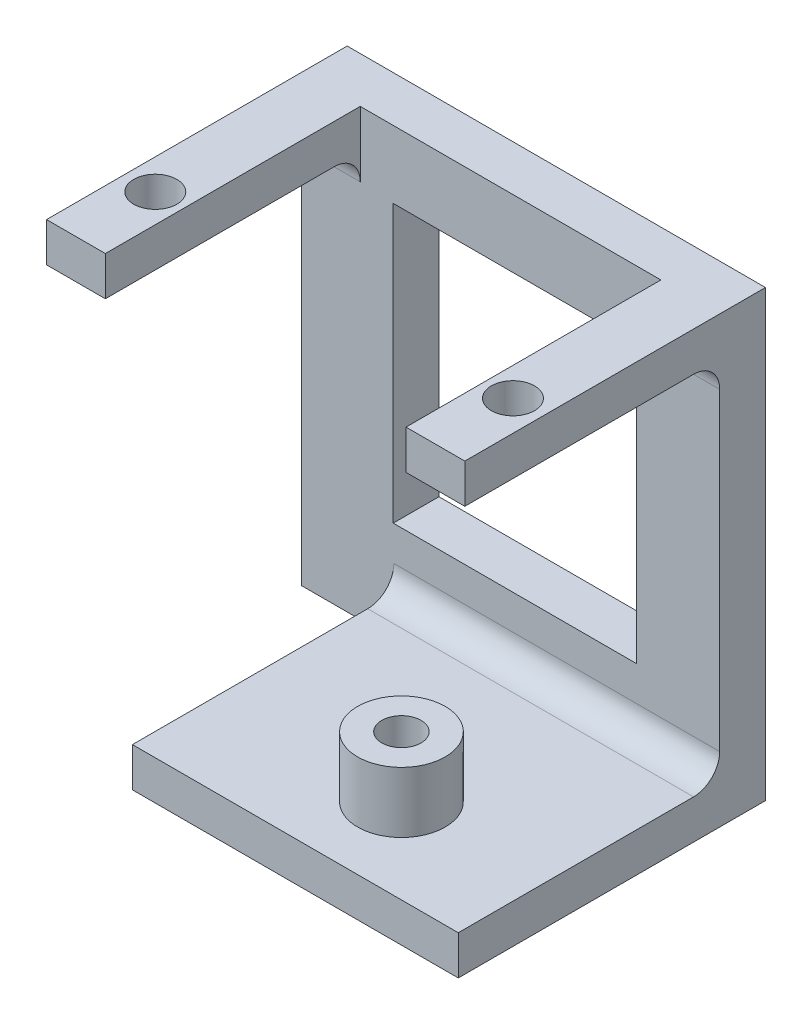
SolidWorks part; units mm, degrees
ref_plane "前视基准面" through (0, 0, 0) normal (0, 0, 1) x (1, 0, 0)
ref_plane "上视基准面" through (0, 0, 0) normal (0, 1, 0) x (1, 0, 0)
ref_plane "右视基准面" through (0, 0, 0) normal (1, 0, 0) x (0, 0, -1)
sketch "草图1" plane through (0, 0, 0) normal (0, 1, 0) x (1, 0, 0)
  line L0 (0, 5.3451) -> (0, 14.3596) construction
  line L13 (-16, 17) -> (-11.5, 17)
  line L14 (-16, 17) -> (-16, -6)
  line L19 (-16, -6) -> (-11.5, -6)
  line L20 (-11.5, 17) -> (-11.5, -6)
  line L21 (-16, 17) -> (-11.5, -6) construction
  line L22 (-16, -6) -> (-11.5, 17) construction
  line L23 (11.5, 17) -> (16, 17)
  line L24 (11.5, 17) -> (11.5, -6)
  line L25 (11.5, -6) -> (16, -6)
  line L26 (16, 17) -> (16, -6)
  line L27 (11.5, 17) -> (16, -6) construction
  line L28 (11.5, -6) -> (16, 17) construction
  line L29 (-11.5, 12.2078) -> (11.5, 12.2078) construction
  line L30 (0, -55) -> (0, 55) construction
  point P4 (-13.75, 5.5)
  point P9 (13.75, 5.5)
  point P14 (0, 12.2078)
  dimension "D1" = 23
  dimension "D2" = 6
  dimension "D3" = 23
  dimension "D4" = 4.5
extrude "凸台-拉伸1" add sketch "草图1" along normal mid plane 3
sketch "草图2" plane through (0, 0, 0) normal (0, 1, 0) x (1, 0, 0)
  line L0 (-13.68, 0) -> (13.68, 0) construction
  circle A0 centre (-13.68, 0) radius 1.65
  circle A1 centre (13.68, 0) radius 1.65
  point P3 (0, 0)
  dimension "D2" = 3.3
  dimension "D3" = 3.3
  dimension "D1" = 27.36
extrude "切除-拉伸1" cut sketch "草图2" against normal through all both and the other way through all
sketch "草图4" plane through (-11.5, 0, 0) normal (1, 0, 0) x (0, 0, -1)
  line L0 (-6, -1.5) -> (17, -1.5) construction
  line L1 (17, 1.5) -> (13.5, 1.5)
  line L2 (17, 1.5) -> (17, -1.5)
  line L3 (17, -1.5) -> (13.5, -1.5)
  line L4 (13.5, 1.5) -> (13.5, -1.5)
  line L5 (17, 1.5) -> (13.5, -1.5) construction
  line L6 (17, -1.5) -> (13.5, 1.5) construction
  point P4 (15.25, 0)
  dimension "D1" = 3.5
extrude "凸台-拉伸3" add sketch "草图4" along normal up to next (23 mm away)
sketch "草图3" plane through (-11.5, 0, 0) normal (1, 0, 0) x (0, 0, -1)
  line L0 (-6, 1.5) -> (17, 1.5) construction
  line L1 (6.5, 1.5) -> (8.5, 1.5)
  line L2 (6.5, 1.5) -> (6.5, -1.5)
  line L3 (6.5, -1.5) -> (8.5, -1.5)
  line L4 (8.5, 1.5) -> (8.5, -1.5)
  line L5 (6.5, 1.5) -> (8.5, -1.5) construction
  line L6 (6.5, -1.5) -> (8.5, 1.5) construction
  line L7 (-6, -1.5) -> (17, -1.5) construction
  line L8 (-6, 1.5) -> (-6, -1.5) construction
  point P4 (7.5, 0)
  dimension "D1" = 12.5
  dimension "D2" = 2
sketch "草图5" plane through (0, -1.5, 0) normal (0, -1, 0) x (-1, 0, 0)
  line L1 (-16, 13.5) -> (16, 13.5)
  line L2 (-16, 13.5) -> (-16, 17)
  line L3 (-16, 17) -> (16, 17)
  line L4 (16, 13.5) -> (16, 17)
  line L5 (-16, 13.5) -> (16, 17) construction
  line L6 (-16, 17) -> (16, 13.5) construction
  line L7 (-11.5, 13.5) -> (11.5, 13.5) construction
  line L42 (-16, 17) -> (-16, -6) construction
  point P4 (0, 15.25)
  point P10 (-11.3795, 15.5)
  point P11 (-11.3795, 19)
  point P12 (-11.3795, 19)
  point P13 (-11.3795, 15.5)
  point P14 (-11.3795, 19)
  point P15 (11.6205, 19)
  point P16 (-11.3795, 15.5)
  point P17 (11.6205, 15.5)
  point P18 (-11.3795, 15.5)
  point P19 (11.6205, 15.5)
  point P20 (-11.3795, 19)
  point P21 (11.6205, 19)
  point P22 (11.6205, 19)
  point P23 (11.6205, 15.5)
  point P24 (11.6205, 15.5)
  point P25 (11.6205, 19)
  point P26 (11.6205, 19)
  point P27 (16.4112, 19)
  point P28 (11.6205, -6)
  point P29 (11.6205, 19)
  point P30 (16.4112, -6)
  point P31 (11.6205, -6)
  point P32 (16.4112, 19)
  point P33 (16.4112, -6)
  point P34 (11.6205, 19)
  point P35 (16.4112, 19)
  point P36 (11.6205, -6)
  point P37 (11.6205, 19)
  point P38 (16.4112, -6)
  point P39 (11.6205, -6)
  point P40 (16.4112, 19)
  point P41 (16.4112, -6)
  point P42 (13.68, 0)
  point P43 (15.2579, 0.4824)
  point P44 (13.68, 0)
  point P45 (15.2579, 0.4824)
  point P46 (-11.3795, 19)
  point P47 (-11.3795, -6)
  point P48 (-11.3795, -6)
  point P49 (-16.1703, -6)
  point P50 (-16.1703, -6)
  point P51 (-16.1703, 19)
  point P52 (-16.1703, 19)
  point P53 (-11.3795, 19)
  point P54 (-11.3795, 19)
  point P55 (-11.3795, -6)
  point P56 (-11.3795, -6)
  point P57 (-16.1703, -6)
  point P58 (-16.1703, -6)
  point P59 (-16.1703, 19)
  point P60 (-16.1703, 19)
  point P61 (-11.3795, 19)
  point P62 (-13.68, 0)
  point P63 (-12.1021, 0.4824)
  point P64 (-13.68, 0)
  point P65 (-12.1021, 0.4824)
  point P66 (0.1205, -199992.6549)
  point P67 (0.1205, 200016.3596)
  point P68 (16.4112, 19)
  point P69 (11.6205, 19)
  point P70 (16.4112, 19)
  point P71 (16.4112, -6)
  point P72 (16.4112, -6)
  point P73 (11.6205, -6)
  point P74 (11.6205, 19)
  point P75 (11.6205, -6)
  point P76 (16.4112, 19)
  point P77 (11.6205, -6)
  point P78 (16.4112, -6)
  point P79 (11.6205, 19)
  point P80 (-11.3795, 19)
  point P81 (-16.1703, 19)
  point P82 (-11.3795, 19)
  point P83 (-11.3795, -6)
  point P84 (-11.3795, -6)
  point P85 (-16.1703, -6)
extrude "凸台-拉伸4" add sketch "草图5" along normal blind 31
sketch "草图6" plane through (0, 0, -13.5) normal (0, 0, 1) x (1, 0, 0)
  line L0 (-16, -32.5) -> (-16, -1.5) construction
  line L1 (-16, -29.5) -> (16, -29.5)
  line L2 (-16, -29.5) -> (-16, -32.5)
  line L3 (-16, -32.5) -> (16, -32.5)
  line L4 (16, -29.5) -> (16, -32.5)
  line L5 (-16, -29.5) -> (16, -32.5) construction
  line L6 (-16, -32.5) -> (16, -29.5) construction
  point P4 (0, -31)
  dimension "D1" = 3
extrude "凸台-拉伸5" add sketch "草图6" along normal blind 20
sketch "草图7" plane through (0, -29.5, 0) normal (0, 1, 0) x (1, 0, 0)
  line L0 (-13.68, 0) -> (13.68, 0) construction
  point P0 (0, 0)
  point P1 (5.15, 0)
  point P6 (0, 0)
  dimension "D1" = 27.36
  dimension "D2" = 8.53
sketch "草图8" plane through (0, -29.5, 0) normal (0, 1, 0) x (1, 0, 0)
  circle A0 centre (5.15, 0) radius 3.35
  dimension "D1" = 6.7
extrude "凸台-拉伸6" add sketch "草图8" along normal blind 6
sketch "草图9" plane through (0, -23.5, 0) normal (0, 1, 0) x (1, 0, 0)
  circle A0 centre (5.15, 0) radius 1.5
  dimension "D1" = 3
extrude "切除-拉伸2" cut sketch "草图9" against normal up to next
sketch "草图10" plane through (0, 0, -17) normal (0, 0, -1) x (-1, 0, 0)
  line L1 (-9.6277, -3.6672) -> (8.9791, -3.6672)
  line L2 (-9.6277, -3.6672) -> (-9.6277, -24.8524)
  line L3 (-9.6277, -24.8524) -> (8.9791, -24.8524)
  line L4 (8.9791, -3.6672) -> (8.9791, -24.8524)
  line L5 (-9.6277, -3.6672) -> (8.9791, -24.8524) construction
  line L6 (-9.6277, -24.8524) -> (8.9791, -3.6672) construction
  point P4 (-0.3243, -14.2598)
extrude "切除-拉伸3" cut sketch "草图10" against normal through all
sketch "草图11" plane through (0, -29.5, 0) normal (0, 1, 0) x (1, 0, 0)
  line L0 (16, -6.5) -> (-16, -6.5) construction
  line L5 (-16, 13.5) -> (-8.9302, 13.5)
  line L6 (-16, 13.5) -> (-16, -6.5)
  line L7 (-16, -6.5) -> (-8.9302, -6.5)
  line L8 (-8.9302, 13.5) -> (-8.9302, -6.5)
  line L9 (-16, 13.5) -> (-8.9302, -6.5) construction
  line L10 (-16, -6.5) -> (-8.9302, 13.5) construction
  point P4 (-12.4651, 3.5)
extrude "切除-拉伸4" cut sketch "草图11" against normal blind 10
fillet "圆角1" radius 2 3 edges at (3.5349, -29.5, -13.5) (13.75, -1.5, -13.5) (-13.75, -1.5, -13.5)
